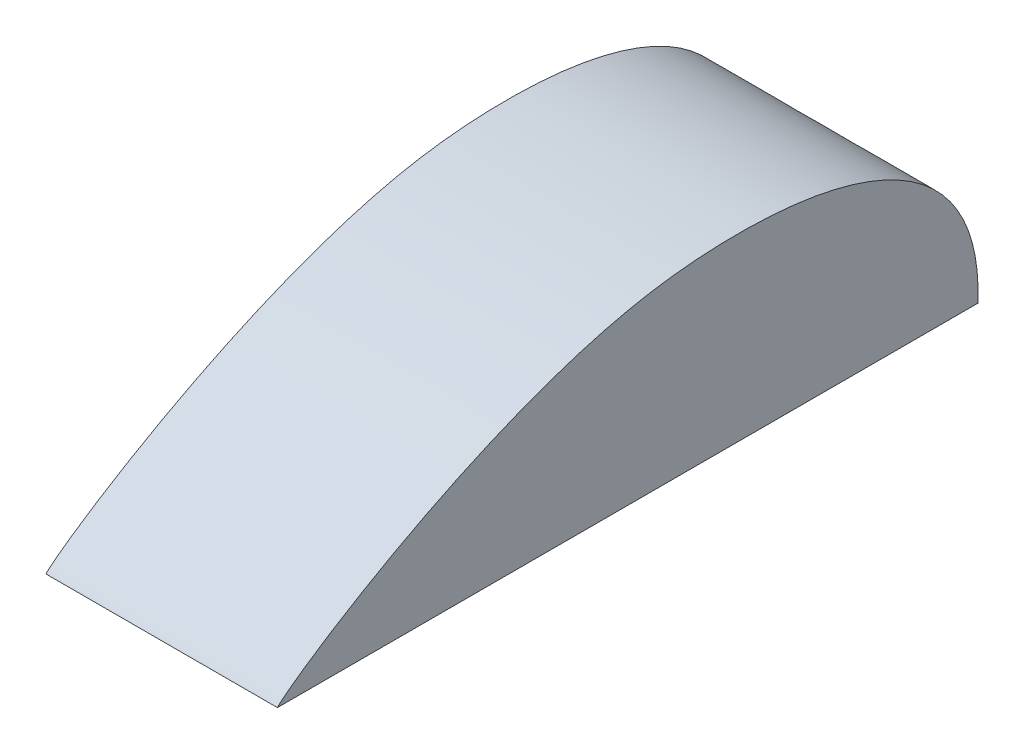
SolidWorks part; units mm, degrees
ref_plane "Front Plane" through (0, 0, 0) normal (0, 0, 1) x (1, 0, 0)
ref_plane "Top Plane" through (0, 0, 0) normal (0, 1, 0) x (1, 0, 0)
ref_plane "Right Plane" through (0, 0, 0) normal (1, 0, 0) x (0, 0, -1)
sketch "Sketch1" plane through (0, 0, 0) normal (1, 0, 0) x (0, 0, -1)
  line L0 (-142.24, 0) -> (142.24, 0)
  spline S0 degree 3 poles (-142.24, 0) (-138.3226, 5.3748) (-50.6709, 65.1397) (83.4191, 78.1984) (144.251, 56.5905) (142.24, 0) knots 0 0 0 0 0.497311 0.584328 1 1 1 1
  point P3 (0, 0)
  point P5 (26.5132, 72.39)
  point P7 (130.2704, 42.2873)
  point P8 (32.3408, 73.8488)
  point P9 (0, 0)
  point P10 (0, 0)
  dimension "D2" = 72.39
  dimension "D1" = 284.48
extrude "Boss-Extrude1" add sketch "Sketch1" along normal mid plane 93.98
